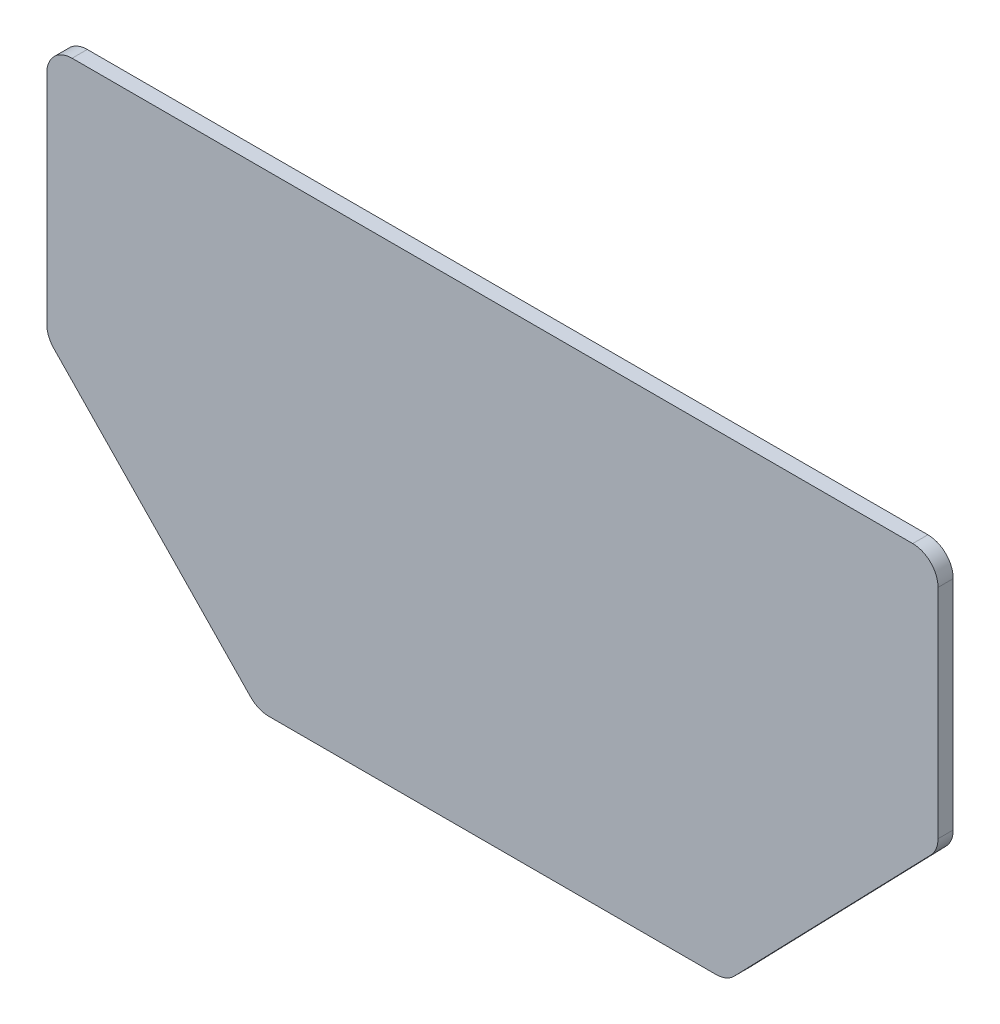
SolidWorks part; units mm, degrees
ref_plane "Plan de face" through (0, 0, 0) normal (0, 0, 1) x (1, 0, 0)
ref_plane "Plan de dessus" through (0, 0, 0) normal (0, 1, 0) x (1, 0, 0)
ref_plane "Plan de droite" through (0, 0, 0) normal (1, 0, 0) x (0, 0, -1)
sketch "Esquisse1" plane through (0, 0, 0) normal (0, 0, 1) x (1, 0, 0)
  line L0 (-176, 100) -> (-176, 0)
  line L1 (-176, 0) -> (-92.57, -86.25)
  line L2 (-92.57, -86.25) -> (92.57, -86.25)
  line L3 (92.57, -86.25) -> (176, 0)
  line L4 (176, 0) -> (176, 100)
  line L5 (176, 100) -> (-176, 100)
  point P6 (0, 100)
  dimension "D1" = 352
  dimension "D2" = 100
  dimension "D3" = 83.43
  dimension "D4" = 186.25
extrude "Boss.-Extru.1" add sketch "Esquisse1" along normal blind 6
fillet "Congé1" radius 10 6 edges at (-176, 0, 3) (-92.57, -86.25, 3) (92.57, -86.25, 3) (176, 0, 3) (176, 100, 3) (-176, 100, 3)
sketch "Esquisse2" plane through (0, 0, 6) normal (0, 0, 1) x (1, 0, 0)
  line L0 (0, 6.875) -> (0, -86.25) construction
  line L1 (-88.3302, -86.25) -> (88.3302, -86.25) construction
  line L2 (0, 6.875) -> (0, 100) construction
  line L3 (166, 100) -> (-166, 100) construction
  circle A0 centre (0, 6.875) radius 45
  dimension "D1" = 90
